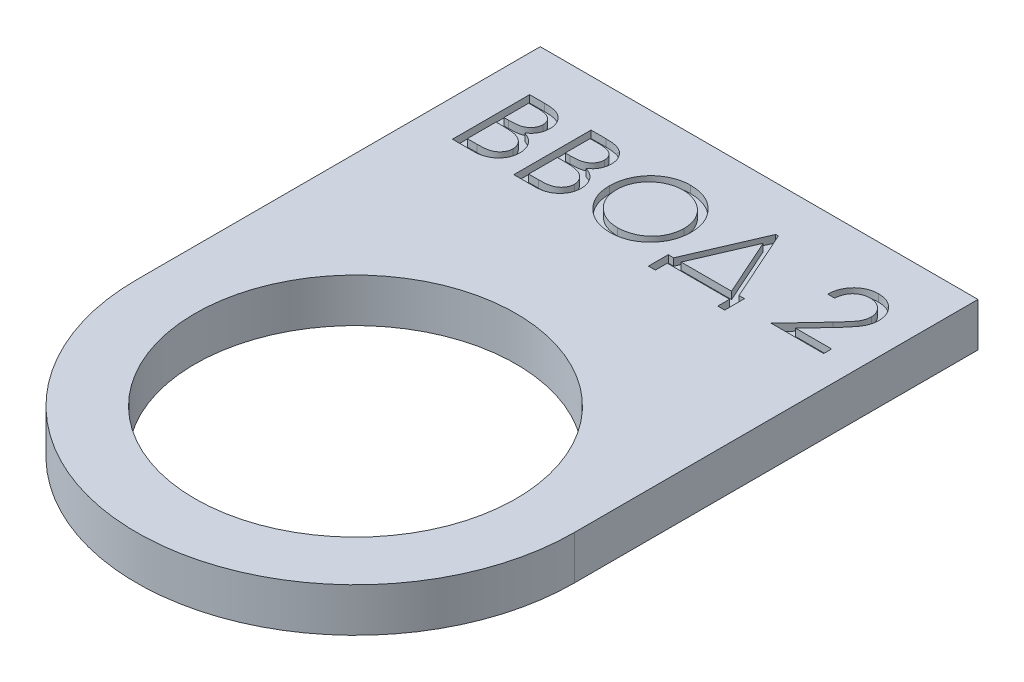
SolidWorks part; units mm, degrees
ref_plane "Front Plane" through (0, 0, 0) normal (0, 0, 1) x (1, 0, 0)
ref_plane "Top Plane" through (0, 0, 0) normal (0, 1, 0) x (1, 0, 0)
ref_plane "Right Plane" through (0, 0, 0) normal (1, 0, 0) x (0, 0, -1)
sketch "Sketch1" plane through (0, 0, 0) normal (0, 1, 0) x (1, 0, 0)
  line L0 (-19.7525, -10.1623) -> (19.1814, -10.1623) construction
  line L1 (15, 17.5) -> (-15, 17.5)
  line L2 (15, 17.5) -> (15, -10.1623)
  line L4 (-15, 17.5) -> (-15, -10.1623)
  line L5 (0, 15.6015) -> (0, -29.3739) construction
  line L6 (-18.6113, 0) -> (19.987, 0) construction
  arc A0 (-15, -10.1623) -> (15, -10.1623) centre (0, -10.1623) ccw
  circle A1 centre (0, -10.1623) radius 11
  point P0 (0, 0)
  dimension "D1" = 22
  dimension "D3" = 15
  dimension "D2" = 17.5
extrude "Boss-Extrude1" add sketch "Sketch1" along normal mid plane 3
sketch "Sketch2" plane through (0, 1.5, 0) normal (0, 1, 0) x (1, 0, 0)
  line L0 (15, 9) -> (-15, 9) construction
  line L1 (-15, 17.5) -> (-15, -10.1623) construction
  line L2 (15, 17.5) -> (-15, 17.5) construction
  line L3 (15, -10.1623) -> (15, 17.5) construction
  text T0 "ВВОД 2" font "Century Gothic" height in points 20
  dimension "D1" = 8.5
extrude "Cut-Extrude1" cut sketch "Sketch2" against normal blind 0.5
